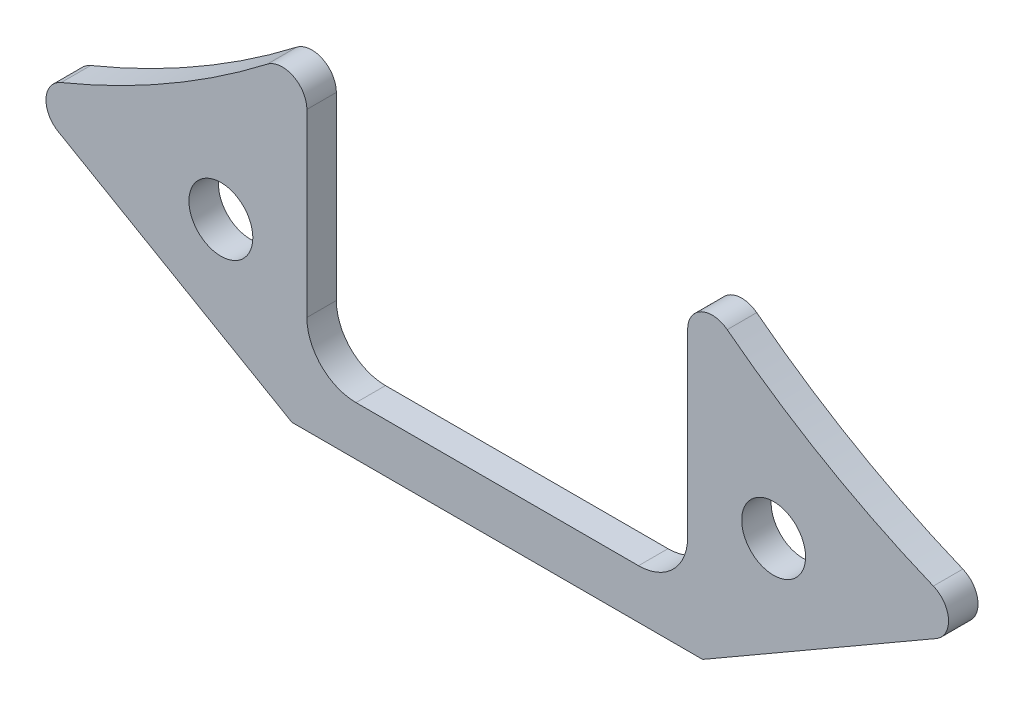
SolidWorks part; units mm, degrees
material "1060 合金"
ref_plane "正面" through (0, 0, 0) normal (0, 0, 1) x (1, 0, 0)
ref_plane "平面" through (0, 0, 0) normal (0, 1, 0) x (1, 0, 0)
ref_plane "右側面" through (0, 0, 0) normal (1, 0, 0) x (0, 0, -1)
sketch "ｽｹｯﾁ2" plane through (0, 0, 0) normal (0, 0, 1) x (1, 0, 0)
  circle A0 centre (0, 0) radius 30.8 construction
  circle A1 centre (0, 0) radius 28.3
  dimension "D1" = 61.6
  dimension "D2" = 56.6
extrude "ﾎﾞｽ - 押し出し1" add sketch "ｽｹｯﾁ2" along normal blind 1.2
sketch "ｽｹｯﾁ3" plane through (0, 0, 1.2) normal (0, 0, 1) x (1, 0, 0)
  line L0 (0, 0) -> (0, -50000) construction
  line L1 (0.5, 28.3) -> (50000.5, 28.3) construction
  line L2 (-7.75, 30.775) -> (7.75, 30.775)
  line L3 (-7.75, 30.775) -> (-7.75, 24.3)
  line L4 (-7.75, 15.775) -> (7.75, 15.775)
  line L5 (7.75, 30.775) -> (7.75, 24.3)
  line L6 (-7.75, 30.775) -> (7.75, 15.775) construction
  line L7 (-7.75, 15.775) -> (7.75, 30.775) construction
  line L8 (-10, 24.3) -> (-7.75, 24.3)
  line L9 (-10, 24.3) -> (-10, 22.25)
  line L10 (-10, 22.25) -> (-7.75, 22.25)
  line L11 (10, 24.3) -> (10, 22.25)
  line L12 (-10, 24.3) -> (10, 22.25) construction
  line L13 (-10, 22.25) -> (10, 24.3) construction
  line L14 (7.75, 22.25) -> (7.75, 15.775)
  line L15 (7.75, 24.3) -> (10, 24.3)
  line L16 (7.75, 22.25) -> (10, 22.25)
  line L17 (-7.75, 22.25) -> (-7.75, 15.775)
  circle A0 centre (0, 0) radius 28.3 construction
  point P3 (0, 23.275)
  point P8 (0, 23.275)
  dimension "D1" = 2.05
  dimension "D2" = 15.5
  dimension "D3" = 15
  dimension "D4" = 4
  dimension "D5" = 20
extrude "ｶｯﾄ - 押し出し1" cut sketch "ｽｹｯﾁ3" against normal through all
fillet "ﾌｨﾚｯﾄ1" radius 2 2 edges at (7.75, 15.775, 0.6) (-7.75, 15.775, 0.6)
fillet "ﾌｨﾚｯﾄ2" radius 0.2 4 edges at (10, 24.3, 0.6) (10, 22.25, 0.6) (-10, 22.25, 0.6) (-10, 24.3, 0.6)
pattern_circular "円形ﾊﾟﾀｰﾝ2" count 6 over 360 about axis through (0, 0, 0) along (0, 0, 1) of "ｶｯﾄ - 押し出し1", "ﾌｨﾚｯﾄ1", "ﾌｨﾚｯﾄ2"
sketch "ｽｹｯﾁ4" plane through (0, 0, 1.2) normal (0, 0, 1) x (1, 0, 0)
  line L0 (0, 0) -> (-18748.6607, 32473.6328) construction
  arc A0 (-7.75, 27.2181) -> (-19.6966, 20.3208) centre (0, 0) ccw construction
  circle A1 centre (0, 0) radius 22.5 construction
  circle A2 centre (11.25, -19.4856) radius 1.25
  circle A3 centre (11.25, -58.4567) radius 1.25
  circle A4 centre (-22.5, -77.9423) radius 1.25
  circle A5 centre (-56.25, -58.4567) radius 1.25
  circle A6 centre (-56.25, -19.4856) radius 1.25
  circle A7 centre (-22.5, 0) radius 1.25
  circle A8 centre (0, 0) radius 11 construction
  circle A9 centre (5.5, -9.5263) radius 1.5
  circle A10 centre (-11, 0) radius 1.5
  circle A11 centre (5.5, 9.5263) radius 1.5
  point P6 (14.15, -24.5085)
  point P23 (-22.5, -38.9711)
  point P31 (0, 0)
  point P37 (-0.0345, -0.0003)
  dimension "D1" = 2.5
  dimension "D2" = 45
  dimension "D4" = 3
  dimension "D5" = 22
  dimension "D3" = 6
  dimension "D6" = 3
extrude "ｶｯﾄ - 押し出し2" cut sketch "ｽｹｯﾁ4" against normal through all
sketch "ｽｹｯﾁ5" plane through (0, 0, 1.2) normal (0, 0, 1) x (1, 0, 0)
  line L0 (-19.6966, 20.3208) -> (-8.359, 13.775)
  line L1 (-8.359, 13.775) -> (8.359, 13.775)
  line L2 (8.359, 13.775) -> (19.6966, 20.3208)
  line L3 (15.3941, 17.8367) -> (11.5186, 15.5992) construction
  line L4 (-5.75, 15.775) -> (5.75, 15.775) construction
  line L5 (-11.5186, 15.5992) -> (-15.3941, 17.8367) construction
  arc A0 (-19.6966, 20.3208) -> (19.6966, 20.3208) centre (0, 0) ccw
  dimension "D1" = 2
extrude "ｶｯﾄ - 押し出し4" cut sketch "ｽｹｯﾁ5" against normal up to surface (1.2 mm away) up to face at (7, 9.5263, 0)
sketch "ｽｹｯﾁ7" plane through (0, 0, 1.2) normal (0, 0, 1) x (1, 0, 0)
  line L0 (-17.1694, 18.8617) -> (-16.0444, 20.8103)
  line L1 (-16.0444, 20.8103) -> (-14.2691, 19.7853)
  line L2 (-14.2691, 19.7853) -> (-15.3941, 17.8367)
  line L3 (-14.4423, 19.8853) -> (-15.8712, 20.7103) construction
  line L4 (-17.1694, 18.8617) -> (-15.3941, 17.8367)
  line L5 (-8.359, 13.775) -> (-15.3941, 17.8367) construction
  line L6 (0, 13.775) -> (0, 15.775) construction
  line L7 (8.359, 13.775) -> (-8.359, 13.775) construction
  line L8 (-5.75, 15.775) -> (5.75, 15.775) construction
  line L9 (17.1694, 18.8617) -> (15.3941, 17.8367)
  line L10 (14.2691, 19.7853) -> (15.3941, 17.8367)
  line L11 (16.0444, 20.8103) -> (14.2691, 19.7853)
  line L12 (17.1694, 18.8617) -> (16.0444, 20.8103)
  line L13 (-9.8, 22.25) -> (-7.75, 22.25) construction
  line L14 (-7.75, 24.3) -> (-10, 24.3)
  line L15 (-7.75, 24.3) -> (-7.75, 22.25)
  line L16 (-7.75, 22.25) -> (-10, 22.25)
  line L17 (-10, 24.3) -> (-10, 22.25)
  line L18 (-10, 24.1) -> (-10, 22.45) construction
  line L19 (10, 24.3) -> (10, 22.25)
  line L20 (7.75, 22.25) -> (10, 22.25)
  line L21 (7.75, 24.3) -> (7.75, 22.25)
  line L22 (7.75, 24.3) -> (10, 24.3)
extrude "ﾎﾞｽ - 押し出し2" add sketch "ｽｹｯﾁ7" against normal up to surface (1.2 mm away) up to face at (0, 20.7326, 0)
sketch "ｽｹｯﾁ8" plane through (0, 0, 1.2) normal (0, 0, 1) x (1, 0, 0)
  line L0 (0, 0) -> (0, 22.5) construction
  line L1 (-11.25, 19.4856) -> (0, 0) construction
  line L2 (0, 0) -> (11.25, 19.4856) construction
  circle A0 centre (0, 0) radius 22.5 construction
  circle A1 centre (11.25, 19.4856) radius 1.3
  circle A2 centre (-11.25, 19.4856) radius 1.3
  dimension "D1" = 45
  dimension "D2" = 2.6
  dimension "D3" = 60
extrude "ｶｯﾄ - 押し出し6" cut sketch "ｽｹｯﾁ8" against normal up to surface (1.2 mm away) up to face at (0, 19.0378, 0)
sketch "ｽｹｯﾁ9" plane through (0, 0, 1.2) normal (0, 0, 1) x (1, 0, 0)
  line L0 (0, 28.3) -> (0, 13.775) construction
  line L1 (8.359, 13.775) -> (-8.359, 13.775) construction
  line L2 (0, 0) -> (14.15, -24.5085) construction
  line L5 (0, 0) -> (-14.15, 24.5085) construction
  circle A0 centre (0, 0) radius 28.3 construction
  arc A1 (0, 73.0215) -> (0, 36.6173) centre (31.65, 54.8194) cw
  arc A3 (-7.75, 27.2181) -> (-19.6966, 20.3208) centre (0, 0) ccw construction
  arc A4 (0, 73.0215) -> (0, 36.6173) centre (-31.65, 54.8194) ccw
  dimension "D2" = 56.6
  dimension "D1" = 35
extrude "ｶｯﾄ - 押し出し7" cut sketch "ｽｹｯﾁ9" against normal up to surface (1.2 mm away) up to face at (-9.95, 19.4856, 0)
fillet "ﾌｨﾚｯﾄ4" radius 1 4 edges at (19.6966, 20.3208, 0.6) (7.75, 27.2181, 0.6) (-19.6966, 20.3208, 0.6) (-7.75, 27.2181, 0.6)
